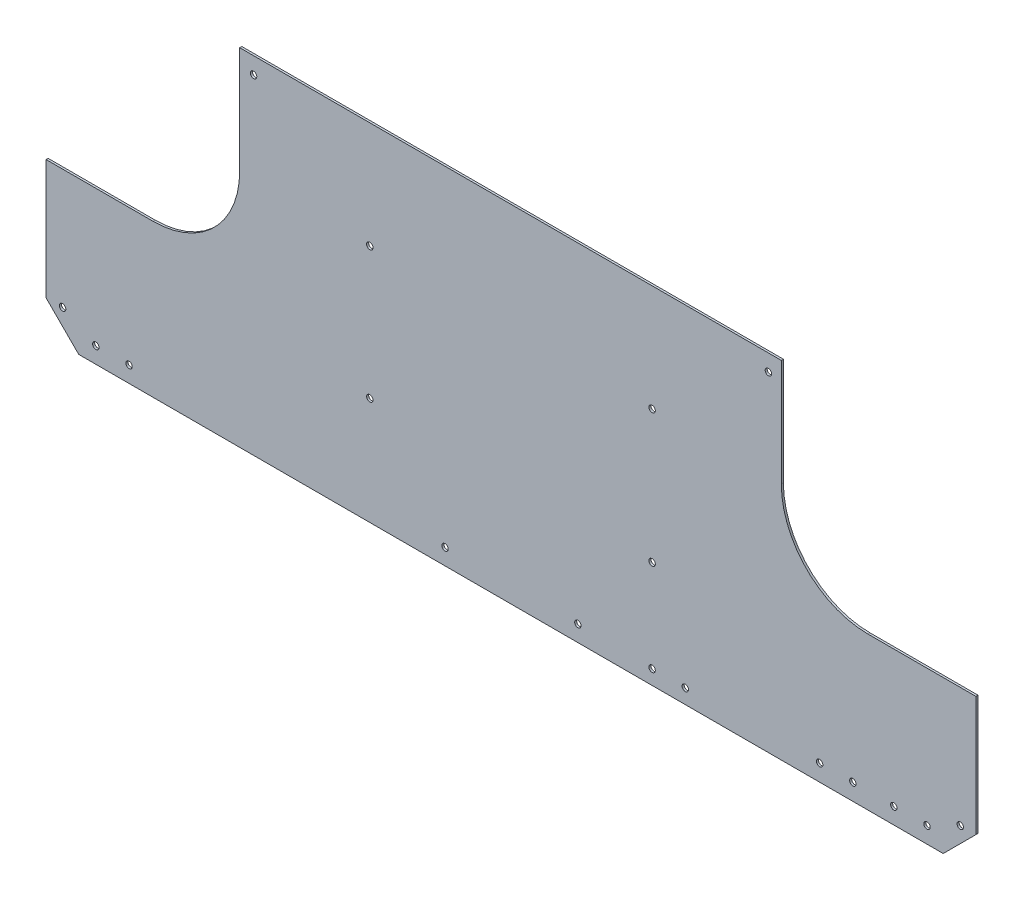
SolidWorks part; units mm, degrees
material "Perspex (TM) GS Acrylic Cast Sheet"
ref_plane "Front Plane" through (0, 0, 0) normal (0, 0, 1) x (1, 0, 0)
ref_plane "Top Plane" through (0, 0, 0) normal (0, 1, 0) x (1, 0, 0)
ref_plane "Right Plane" through (0, 0, 0) normal (1, 0, 0) x (0, 0, -1)
sketch "Sketch1" plane through (0, 0, 0) normal (0, 0, 1) x (1, 0, 0)
  line L1 (-457.2, -304.8) -> (457.2, -304.8)
  line L2 (-457.2, -304.8) -> (-457.2, 304.8)
  line L3 (-457.2, 304.8) -> (457.2, 304.8)
  line L4 (457.2, -304.8) -> (457.2, 304.8)
  line L5 (0, 304.8) -> (0, -304.8) construction
  line L6 (-457.2, 0) -> (457.2, 0) construction
  point P0 (0, 0)
  point P4 (-320.04, 0)
  point P5 (320.04, 0)
  point P6 (0, 213.36)
  point P7 (0, -213.36)
  dimension "Length" = 914.4
  dimension "Width" = 609.6
  dimension "Break" = 137.16
  dimension "D2" = 137.16
  dimension "D1" = 91.44
  dimension "D3" = 91.44
sketch "Sketch2" plane through (0, 0, 0) normal (1, 0, 0) x (0, 0, -1)
  line L0 (-0.7938, -304.8) -> (0.7938, -304.8)
  dimension "Thickness" = 1.5875
sketch "Sketch3" plane through (0, 0, 0) normal (0, 0, 1) x (1, 0, 0)
  line L0 (-457.2, -304.8) -> (-457.2, 304.8) construction
  line L1 (-457.2, -304.8) -> (457.2, -304.8) construction
  line L2 (457.2, -304.8) -> (457.2, 304.8) construction
  line L3 (-457.2, 304.8) -> (457.2, 304.8) construction
  line L4 (-457.2, -304.8) -> (-457.2, 304.8)
  line L5 (-457.2, -304.8) -> (457.2, -304.8)
  line L6 (457.2, -304.8) -> (457.2, 304.8)
  line L7 (-457.2, 304.8) -> (457.2, 304.8)
extrude "Boss-Extrude1" add sketch "Sketch3" along normal mid plane 1.5875
sketch "Sketch4" plane through (0, 0, 0.7937) normal (0, 0, 1) x (1, 0, 0)
  line L17 (-352.1349, -305.1706) -> (-377.5349, -279.7706)
  line L18 (-377.5349, -751.2581) -> (-377.5349, -65.4581) construction
  line L19 (-377.5349, -279.7706) -> (-377.5349, -42.5981)
  line L20 (-374.9949, -40.0581) -> (331.1251, -40.0581)
  line L21 (-352.1349, -305.1706) -> (308.2651, -305.1706)
  line L22 (308.2651, -40.0581) -> (308.2651, -725.8581) construction
  line L23 (308.9763, -305.1706) -> (-352.1349, -305.1706) construction
  line L24 (308.2651, -305.1706) -> (333.6651, -279.7706)
  line L25 (333.6651, -40.0581) -> (333.6651, -725.8581) construction
  line L26 (333.6651, -279.7706) -> (333.6651, -42.5981)
  arc A0 (333.6651, -42.5981) -> (331.1251, -40.0581) centre (331.1251, -42.5981) ccw
  arc A1 (-374.9949, -40.0581) -> (-377.5349, -42.5981) centre (-374.9949, -42.5981) ccw
  point P20 (333.6651, -40.0581)
  point P23 (-377.5349, -40.0581)
  dimension "D1" = 2.54
  dimension "D2" = 2.54
extrude "Cut-Extrude1" cut sketch "Sketch4" against normal blind 2.54 flip side to cut
sketch "Sketch7" plane through (0, 0, 0.7937) normal (0, 0, 1) x (1, 0, 0)
  line L0 (-377.5349, -188.1903) -> (-377.5349, -40.0581)
  line L3 (-377.5349, -40.0581) -> (-229.4027, -40.0581)
  line L10 (-229.4027, -64.7463) -> (-229.4027, -40.0581)
  line L11 (-229.4027, -64.7463) -> (-229.4027, -121.8963)
  line L12 (-352.8467, -188.1903) -> (-295.6967, -188.1903)
  line L13 (-352.8467, -188.1903) -> (-377.5349, -188.1903)
  arc A1 (-229.4027, -121.8963) -> (-295.6967, -188.1903) centre (-295.6967, -121.8963) cw
extrude "Cut-Extrude2" cut sketch "Sketch7" against normal blind 2.54
sketch "Sketch8" plane through (0, 0, 0.7937) normal (0, 0, 1) x (1, 0, 0)
  line L6 (251.1151, -188.1903) -> (336.8401, -188.1903)
  line L7 (336.8401, -188.1903) -> (336.8401, -36.1713)
  line L8 (184.8211, -36.1713) -> (336.8401, -36.1713)
  line L9 (184.8211, -121.8963) -> (184.8211, -36.1713)
  arc A1 (184.8211, -121.8963) -> (251.1151, -188.1903) centre (251.1151, -121.8963) ccw
extrude "Cut-Extrude3" cut sketch "Sketch8" against normal blind 2.54
sketch "Sketch9" plane through (0, 0, 0.7937) normal (0, 0, 1) x (1, 0, 0)
  point P0 (-364.8349, -279.7706)
  point P1 (-339.4349, -292.4706)
  point P3 (-314.0349, -292.4706)
  point P5 (-364.8349, -229.8463)
  point P7 (86.0055, -293.7022)
  point P9 (111.4055, -293.7022)
  point P11 (214.1495, -292.1147)
  point P13 (239.5495, -292.1147)
  point P15 (270.8763, -292.4706)
  point P17 (296.2763, -292.4706)
  point P19 (321.6763, -279.7706)
  point P21 (320.9651, -230.5581)
  point P23 (-218.7849, -52.7581)
  point P25 (174.9151, -52.7581)
hole_wizard "#10 (0.1935) Diameter Hole1" positions "Sketch10" profile "Sketch11" hole size "#10" standard "ANSI Inch" end condition through all
sketch "Sketch10" plane through (0, 0, 0.7937) normal (0, 0, 1) x (1, 0, 0)
  point P0 (-314.0349, -292.4706)
  point P3 (-339.4349, -292.4706)
  point P6 (-364.8349, -279.7706)
  point P9 (86.0055, -293.7022)
  point P12 (111.4055, -293.7022)
  point P15 (214.1495, -292.1147)
  point P18 (239.5495, -292.1147)
  point P21 (296.2763, -292.4706)
  point P24 (270.8763, -292.4706)
  point P27 (321.6763, -279.7706)
  point P31 (174.9151, -52.7581)
  point P34 (-218.7849, -52.7581)
  point P37 (-72.3793, -292.4706)
  point P40 (29.2207, -292.4706)
sketch "Sketch11" plane through (-314.0349, -292.4706, 0.7937) normal (1, 0, 0) x (0, -1, 0)
  line L0 (0, 0) -> (0, 1.5875)
  line L1 (0, 1.5875) -> (2.4574, 1.5875)
  line L2 (2.4574, 1.5875) -> (2.4574, 0)
  line L5 (2.4574, 0) -> (0, 0)
  line L11 (0, -6.35) -> (0, 107.95) construction
  dimension "Thru Hole Dia." = 4.9149
  dimension "Thru Hole Depth" = 1.5875
sketch "Sketch12" plane through (0, 0, 0.7937) normal (0, 0, 1) x (1, 0, 0)
  line L0 (-21.9349, -304.8) -> (-21.9349, -40.0581)
  line L1 (-352.5056, -304.8) -> (308.6357, -304.8) construction
  line L3 (-377.5349, -40.0581) -> (308.2651, -40.0581) construction
  line L8 (-129.8849, -223.2291) -> (86.0151, -223.2291)
  line L10 (-129.8849, -223.2291) -> (-129.8849, -121.6291)
  line L11 (-129.8849, -121.6291) -> (86.0151, -121.6291)
  line L12 (86.0151, -223.2291) -> (86.0151, -121.6291)
  line L13 (-129.8849, -223.2291) -> (86.0151, -121.6291) construction
  line L14 (-129.8849, -121.6291) -> (86.0151, -223.2291) construction
  point P6 (-21.9349, -172.4291)
  point P16 (-21.9349, -304.8)
hole_wizard "#10 (0.1935) Diameter Hole2" positions "Sketch13" profile "Sketch14" hole size "#10" standard "ANSI Inch" end condition through all
sketch "Sketch13" plane through (0, 0, 0.7937) normal (0, 0, 1) x (1, 0, 0)
  line L0 (-129.8849, -223.2291) -> (-129.8849, -121.6291) construction
  point P25 (-129.8849, -121.6291)
  point P28 (-129.8849, -222.541)
  point P32 (86.0151, -223.2291)
  point P35 (86.0151, -121.6291)
sketch "Sketch14" plane through (-129.8849, -121.6291, 0.7937) normal (1, 0, 0) x (0, -1, 0)
  line L0 (0, 0) -> (0, 1.5875)
  line L1 (0, 1.5875) -> (2.4574, 1.5875)
  line L2 (2.4574, 1.5875) -> (2.4574, 0)
  line L5 (2.4574, 0) -> (0, 0)
  line L11 (0, -6.35) -> (0, 107.95) construction
  dimension "Thru Hole Dia." = 4.9149
  dimension "Thru Hole Depth" = 1.5875
equation "\"D1@Boss-Extrude1\"=\"thickness@sketch2\""
equation "\"Break@Sketch1\" = \"Length@Sketch1\" * 0.15"
equation "\"D2@Sketch1\" = \"Break@Sketch1\""
equation "\"D1@Sketch1\"=\"Width@Sketch1\"*0.15"
equation "\"D3@Sketch1\"=\"D1@Sketch1\""
